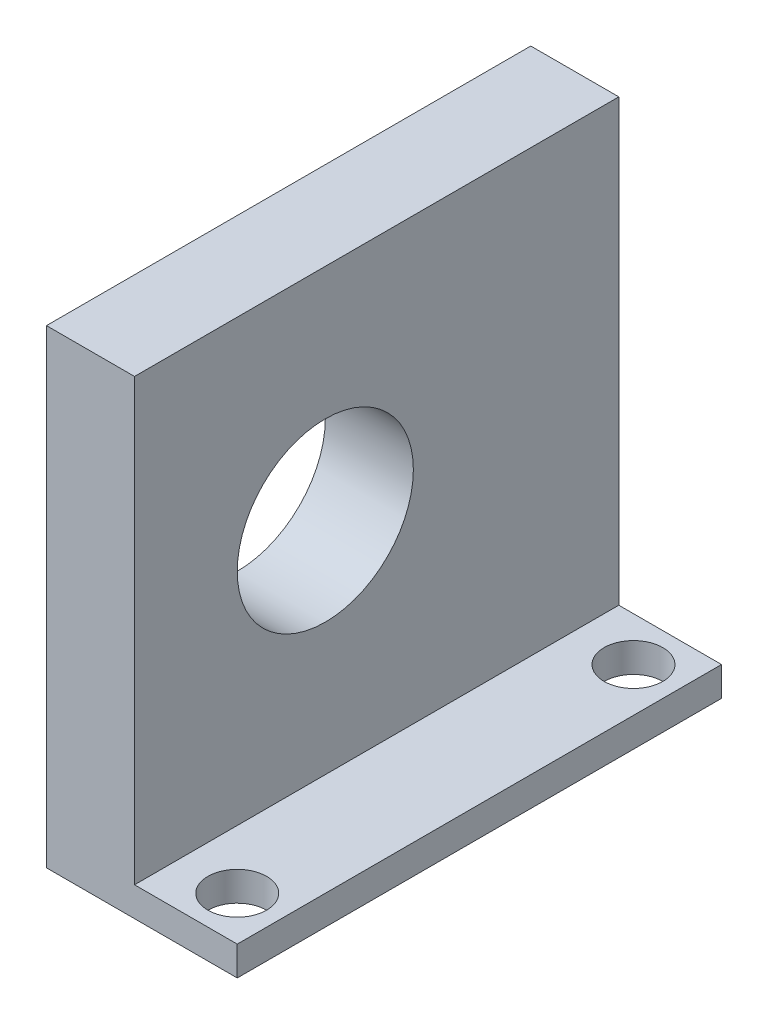
SolidWorks part; units mm, degrees
material "ABS PC"
ref_plane "Front Plane" through (0, 0, 0) normal (0, 0, 1) x (1, 0, 0)
ref_plane "Top Plane" through (0, 0, 0) normal (0, 1, 0) x (1, 0, 0)
ref_plane "Right Plane" through (0, 0, 0) normal (1, 0, 0) x (0, 0, -1)
sketch "Sketch1" plane through (0, 0, 0) normal (0, 0, 1) x (1, 0, 0)
  line L0 (0, 0) -> (0, 32)
  line L1 (0, 32) -> (6, 32)
  line L2 (6, 32) -> (6, 2)
  line L3 (6, 2) -> (13, 2)
  line L4 (13, 2) -> (13, 0)
  line L5 (13, 0) -> (0, 0)
  dimension "D1" = 32
  dimension "D2" = 2
  dimension "D3" = 6
  dimension "D4" = 13
extrude "Boss-Extrude1" add sketch "Sketch1" along normal blind 33
sketch "Sketch2" plane through (6, 0, 0) normal (1, 0, 0) x (0, 0, -1)
  line L0 (-33, 2) -> (-33, 32) construction
  line L1 (-33, 2) -> (0, 2) construction
  circle A0 centre (-20, 17) radius 6
  dimension "D3" = 12
  dimension "D1" = 13
  dimension "D2" = 15
extrude "Cut-Extrude1" cut sketch "Sketch2" against normal up to next
sketch "Sketch3" plane through (0, 2, 0) normal (0, 1, 0) x (1, 0, 0)
  line L0 (13, -33) -> (13, 0) construction
  line L1 (13, -33) -> (6, -33) construction
  line L2 (13, 0) -> (6, 0) construction
  circle A0 centre (10, -3) radius 2
  circle A1 centre (10, -30) radius 2
  dimension "D1" = 4
  dimension "D2" = 4
  dimension "D3" = 3
  dimension "D4" = 3
  dimension "D5" = 3
  dimension "D6" = 3
extrude "Cut-Extrude2" cut sketch "Sketch3" against normal up to next
